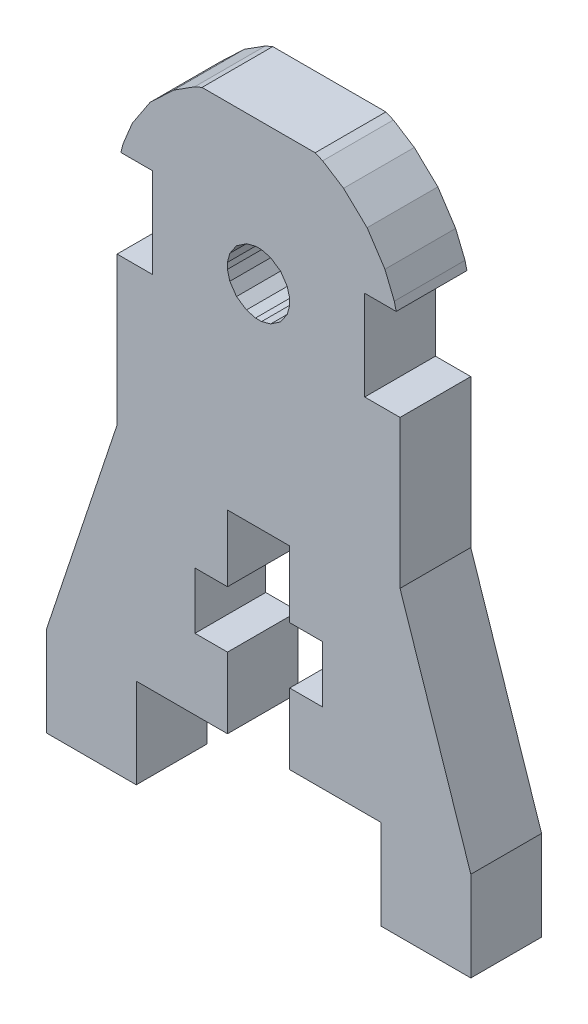
SolidWorks part; units mm, degrees
material "Balsa"
ref_plane "Front Plane" through (0, 0, 0) normal (0, 0, 1) x (1, 0, 0)
ref_plane "Top Plane" through (0, 0, 0) normal (0, 1, 0) x (1, 0, 0)
ref_plane "Right Plane" through (0, 0, 0) normal (1, 0, 0) x (0, 0, -1)
sketch "Sketch1" plane through (0, 0, 0) normal (0, 0, 1) x (1, 0, 0)
  line L66 (-10.2111, -1.329) -> (-15.2047, -16.3289)
  line L67 (-15.2047, -16.3289) -> (-15.2047, -22.6789)
  line L68 (-10.2111, 9.1346) -> (-10.2111, -1.329)
  line L69 (14.7927, -22.6789) -> (8.4427, -22.6789)
  line L70 (-8.8547, -22.6789) -> (-15.2047, -22.6789)
  line L71 (-8.8547, -16.3289) -> (-2.4057, -16.3289)
  line L72 (1.9885, -16.3289) -> (8.4427, -16.3289)
  line L73 (-8.8547, -16.3289) -> (-8.8547, -22.6789)
  line L74 (-7.7092, 15.4851) -> (-7.7092, 9.1346)
  line L75 (-4.7069, -11.3295) -> (-4.7069, -7.329)
  line L76 (-2.4057, -16.3289) -> (-2.4057, -11.3295)
  line L77 (-2.4057, -7.329) -> (-2.4057, -2.63)
  line L78 (1.9885, -16.3289) -> (1.9885, -11.3295)
  line L79 (1.9885, -7.329) -> (1.9885, -2.63)
  line L80 (-4.7069, -11.3295) -> (-2.4057, -11.3295)
  line L81 (1.9885, -11.3295) -> (4.2923, -11.3295)
  line L82 (-4.7069, -7.329) -> (-2.4057, -7.329)
  line L83 (1.9885, -7.329) -> (4.2923, -7.329)
  line L84 (-2.4057, -2.63) -> (1.9885, -2.63)
  line L85 (4.2923, -11.3295) -> (4.2923, -7.329)
  line L86 (7.292, 9.1346) -> (7.292, 15.4851)
  line L87 (8.4427, -16.3289) -> (8.4427, -22.6789)
  line L88 (9.7889, -1.329) -> (9.7889, 9.1346)
  line L89 (14.7927, -16.3289) -> (14.7927, -22.6789)
  line L90 (-10.2111, 9.1346) -> (-7.7092, 9.1346)
  line L91 (7.292, 9.1346) -> (9.7889, 9.1346)
  line L92 (-9.9393, 15.4851) -> (-7.7092, 15.4851)
  line L93 (7.292, 15.4851) -> (9.5171, 15.4851)
  line L94 (3.7894, 22.3354) -> (-4.2091, 22.3354)
  line L95 (14.7927, -16.3289) -> (9.7889, -1.329)
  line L96 (-4.2091, 22.3354) -> (-4.7374, 22.1068)
  line L97 (-4.7374, 22.1068) -> (-6.2157, 21.167)
  line L98 (-6.2157, 21.167) -> (-7.8819, 19.5846)
  line L99 (-7.8819, 19.5846) -> (-9.1418, 17.6695)
  line L100 (-9.1418, 17.6695) -> (-9.8047, 16.0489)
  line L101 (-9.8047, 16.0489) -> (-9.9393, 15.4851)
  line L102 (9.5171, 15.4851) -> (9.3825, 16.0464)
  line L103 (9.3825, 16.0464) -> (8.7195, 17.6695)
  line L104 (8.7195, 17.6695) -> (7.4597, 19.5846)
  line L105 (7.4597, 19.5846) -> (5.796, 21.1645)
  line L106 (5.796, 21.1645) -> (4.3177, 22.1068)
  line L107 (4.3177, 22.1068) -> (3.7894, 22.3354)
  line L108 (1.9885, 12.3096) -> (1.9885, 12.5242)
  line L109 (1.9885, 12.5242) -> (1.8158, 13.1665)
  line L110 (1.8158, 13.1665) -> (1.3434, 13.8666)
  line L111 (1.3434, 13.8666) -> (0.6449, 14.338)
  line L112 (0.6449, 14.338) -> (0.0022, 14.51)
  line L113 (0.0022, 14.51) -> (-0.2111, 14.51)
  line L114 (-0.2111, 14.51) -> (-0.427, 14.51)
  line L115 (-0.427, 14.51) -> (-1.0696, 14.338)
  line L116 (-1.0696, 14.338) -> (-1.7681, 13.8666)
  line L117 (-1.7681, 13.8666) -> (-2.2406, 13.1665)
  line L118 (-2.2406, 13.1665) -> (-2.4133, 12.5242)
  line L119 (-2.4133, 12.5242) -> (-2.4133, 12.3096)
  line L120 (-2.4133, 12.3096) -> (-2.4133, 12.0957)
  line L121 (-2.4133, 12.0957) -> (-2.2406, 11.4536)
  line L122 (-2.2406, 11.4536) -> (-1.7681, 10.7551)
  line L123 (-1.7681, 10.7551) -> (-1.0696, 10.2836)
  line L124 (-1.0696, 10.2836) -> (-0.427, 10.1102)
  line L125 (-0.427, 10.1102) -> (-0.2111, 10.1102)
  line L126 (-0.2111, 10.1102) -> (0.0022, 10.1102)
  line L127 (0.0022, 10.1102) -> (0.6449, 10.2836)
  line L128 (0.6449, 10.2836) -> (1.3434, 10.7551)
  line L129 (1.3434, 10.7551) -> (1.8158, 11.4536)
  line L130 (1.8158, 11.4536) -> (1.9885, 12.0957)
  line L131 (1.9885, 12.0957) -> (1.9885, 12.3096)
extrude "Boss-Extrude1" add sketch "Sketch1" along normal blind 5
